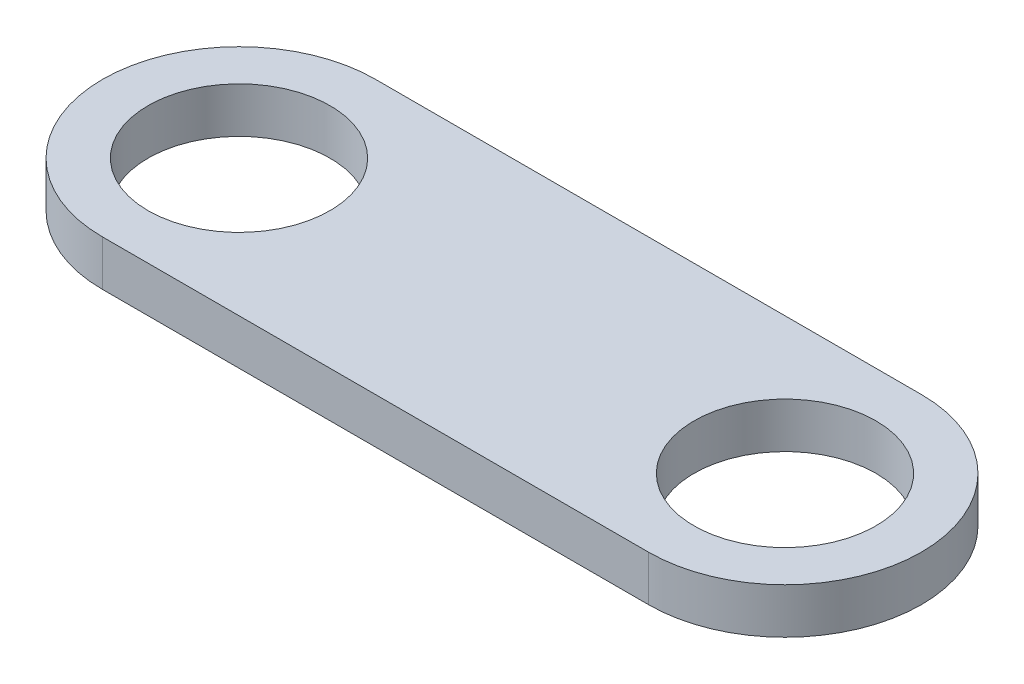
SolidWorks part; units mm, degrees
ref_plane "Płaszczyzna przednia" through (0, 0, 0) normal (0, 0, 1) x (1, 0, 0)
ref_plane "Płaszczyzna górna" through (0, 0, 0) normal (0, 1, 0) x (1, 0, 0)
ref_plane "Płaszczyzna prawa" through (0, 0, 0) normal (1, 0, 0) x (0, 0, -1)
sketch "Sketch1" plane through (0, 0, 0) normal (0, 1, 0) x (1, 0, 0)
  line L0 (0, 3.5025) -> (0, -3.0622) construction
  line L1 (-3, 0) -> (6.3245, 0) construction
  line L2 (-3, 1.5) -> (3, 1.5)
  line L3 (-3, -1.5) -> (3, -1.5)
  arc A0 (-3, 1.5) -> (-3, -1.5) centre (-3, 0) ccw
  arc A1 (3, 1.5) -> (3, -1.5) centre (3, 0) cw
  circle A2 centre (-3, 0) radius 1
  circle A3 centre (3, 0) radius 1
  dimension "D1" = 3
  dimension "D3" = 2
  dimension "D2" = 6
extrude "Boss-Extrude1" add sketch "Sketch1" along normal blind 0.5
